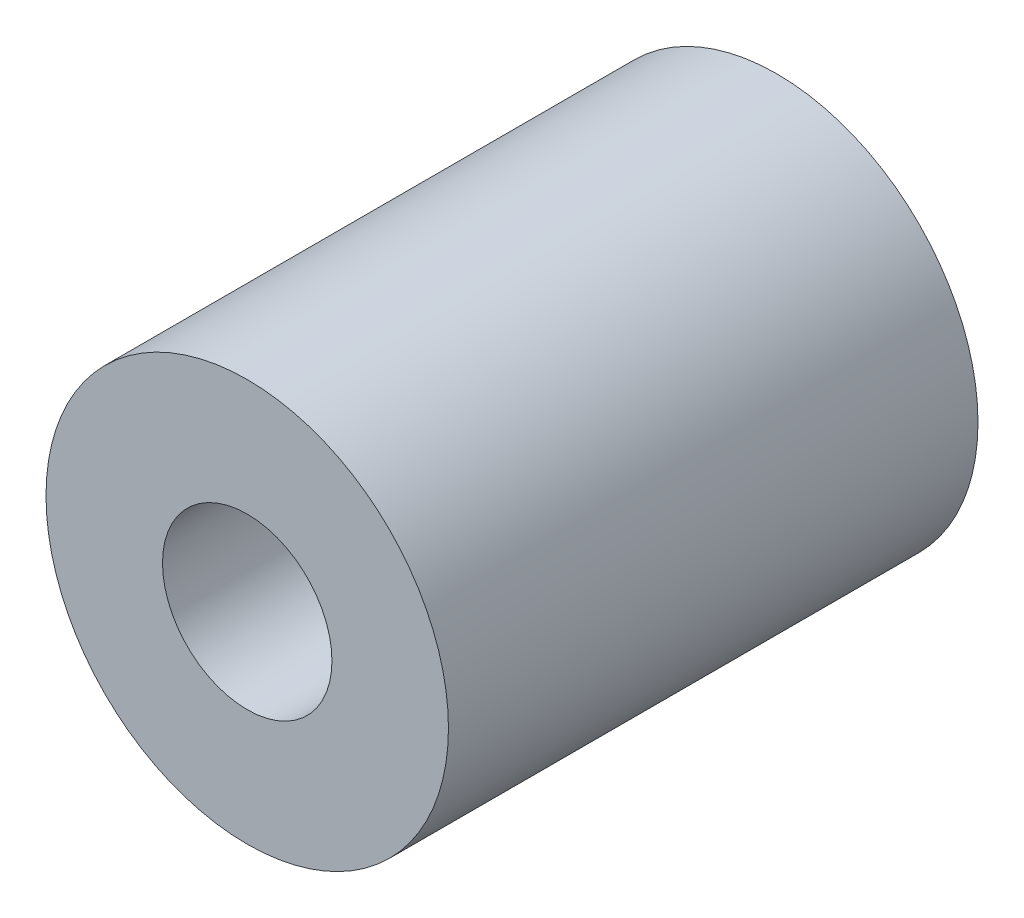
SolidWorks part; units mm, degrees
ref_plane "Front Plane" through (0, 0, 0) normal (0, 0, 1) x (1, 0, 0)
ref_plane "Top Plane" through (0, 0, 0) normal (0, 1, 0) x (1, 0, 0)
ref_plane "Right Plane" through (0, 0, 0) normal (1, 0, 0) x (0, 0, -1)
sketch "Sketch1" plane through (0, 0, 0) normal (0, 0, 1) x (1, 0, 0)
  circle A0 centre (0, 0) radius 9.5
  dimension "D1" = 19
extrude "Boss-Extrude1" add sketch "Sketch1" along normal blind 25
sketch "Sketch2" plane through (0, 0, 25) normal (0, 0, 1) x (1, 0, 0)
  circle A0 centre (0, 0) radius 4
  dimension "D1" = 8
extrude "Cut-Extrude1" cut sketch "Sketch2" against normal blind 12
sketch "Sketch3" plane through (0, 0, 0) normal (0, 0, -1) x (-1, 0, 0)
  circle A0 centre (0, 0) radius 2.5
  dimension "D1" = 5
extrude "Cut-Extrude2" cut sketch "Sketch3" against normal blind 13
